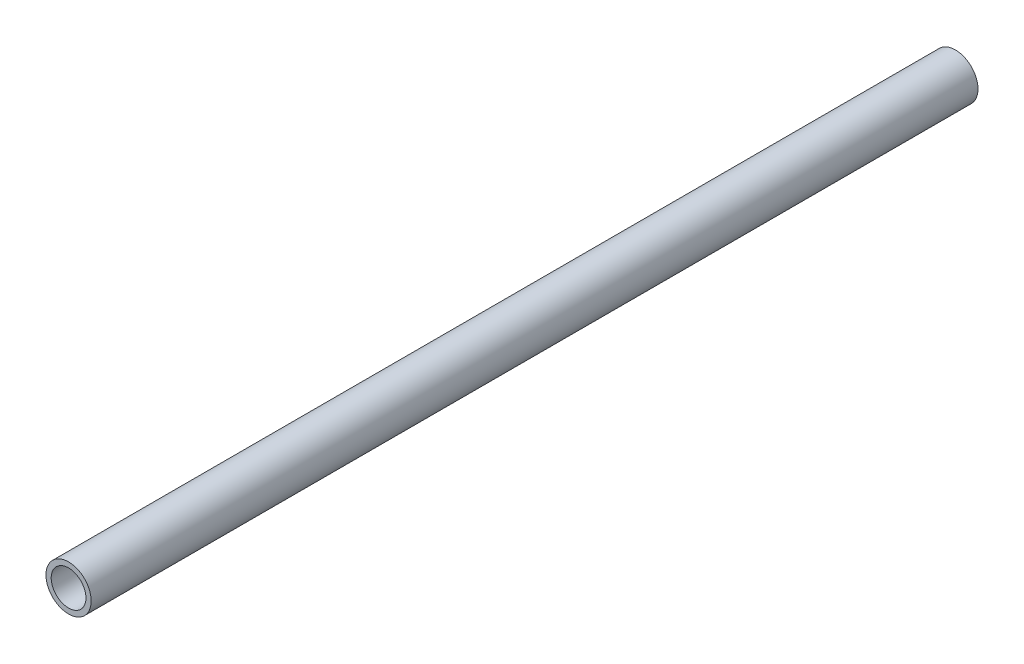
SolidWorks part; units mm, degrees
ref_plane "Front Plane" through (0, 0, 0) normal (0, 0, 1) x (1, 0, 0)
ref_plane "Top Plane" through (0, 0, 0) normal (0, 1, 0) x (1, 0, 0)
ref_plane "Right Plane" through (0, 0, 0) normal (1, 0, 0) x (0, 0, -1)
sketch "Sketch1" plane through (0, 0, 0) normal (0, 0, 1) x (1, 0, 0)
  circle A0 centre (0, 0) radius 16.51
  circle A1 centre (0, 0) radius 12.7
  dimension "D1" = 33.02
  dimension "D2" = 25.4
extrude "Boss-Extrude1" add sketch "Sketch1" along normal blind 647.7
ref_plane "Fitting2" through (0, 0, 647.7) normal (0, 0, 1) x (1, 0, 0)
ref_plane "Fitting1" through (0, 0, 0) normal (0, 0, 1) x (1, 0, 0)
